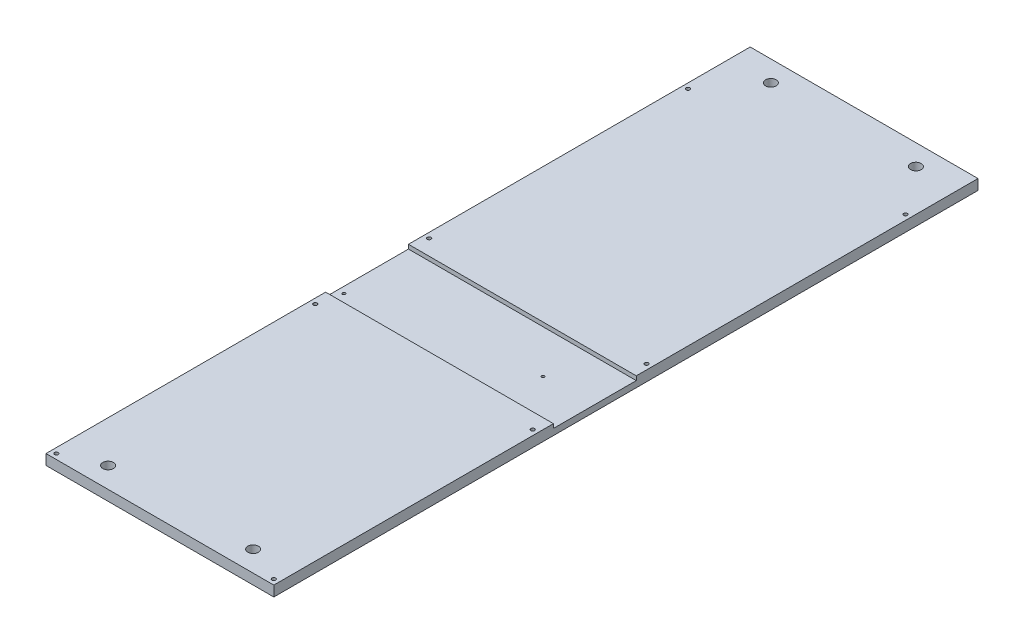
SolidWorks part; units mm, degrees
ref_plane "Front" through (0, 0, 0) normal (0, 0, 1) x (1, 0, 0)
ref_plane "Top" through (0, 0, 0) normal (0, 1, 0) x (1, 0, 0)
ref_plane "Right" through (0, 0, 0) normal (1, 0, 0) x (0, 0, -1)
sketch "Sketch1" plane through (0, 0, 0) normal (0, 1, 0) x (1, 0, 0)
  line L1 (0, 0) -> (139.7, 0)
  line L2 (0, 0) -> (0, 431.8)
  line L3 (0, 431.8) -> (139.7, 431.8)
  line L4 (139.7, 0) -> (139.7, 431.8)
  dimension "D1" = 431.8
  dimension "D2" = 139.7
extrude "Boss-Extrude1" add sketch "Sketch1" along normal blind 6.35
sketch "Sketch3" plane through (0, 6.35, 0) normal (0, 1, 0) x (1, 0, 0)
  line L0 (0, 0) -> (139.7, 0) construction
  line L1 (0, 431.8) -> (0, 0) construction
  line L2 (69.85, 431.8) -> (69.85, 0) construction
  line L3 (139.7, 431.8) -> (0, 431.8) construction
  line L6 (0, 165.1) -> (0, 228.6)
  line L9 (0, 196.85) -> (139.7, 196.85) construction
  circle A0 centre (3.175, 3.175) radius 1.1303
  circle A1 centre (3.175, 161.925) radius 1.1303
  circle A2 centre (3.175, 390.525) radius 1.1303
  circle A3 centre (3.175, 231.775) radius 1.1303
  circle A4 centre (136.525, 3.175) radius 1.1303
  circle A5 centre (136.525, 161.925) radius 1.1303
  circle A6 centre (136.525, 231.775) radius 1.1303
  circle A7 centre (136.525, 390.525) radius 1.1303
  point P24 (0, 0)
  dimension "D1" = 2.2606
  dimension "D2" = 3.175
  dimension "D3" = 3.175
  dimension "D5" = 63.5
  dimension "D4" = 2
extrude "Cut-Extrude6" cut sketch "Sketch3" against normal blind 6.35 contours A0 | A4 | A5 | A6 | A1 | A3 | A2 | A7
sketch "Sketch4" plane through (0, 6.35, 0) normal (0, 1, 0) x (1, 0, 0)
  line L0 (0, 431.8) -> (0, 0) construction
  line L1 (0, 228.6) -> (139.7, 228.6)
  line L2 (0, 228.6) -> (0, 165.1)
  line L3 (0, 165.1) -> (139.7, 165.1)
  line L4 (139.7, 228.6) -> (139.7, 165.1)
  line L5 (139.7, 0) -> (139.7, 431.8) construction
  line L6 (0, 0) -> (139.7, 0) construction
  line L8 (-6.35, 171.45) -> (146.05, 171.45)
  line L9 (-6.35, 171.45) -> (-6.35, 222.25)
  line L10 (-6.35, 222.25) -> (146.05, 222.25)
  line L11 (146.05, 171.45) -> (146.05, 222.25)
  point P14 (-6.35, 196.85)
  point P15 (69.85, 222.25)
  dimension "D1" = 63.5
  dimension "D2" = 165.1
  dimension "D3" = 50.8
  dimension "D4" = 152.4
  dimension "D5" = 31.75
  dimension "D6" = 69.85
extrude "Cut-Extrude7" cut sketch "Sketch4" against normal blind 2.54 contours L10 L2 L8 L4
sketch "Sketch5" plane through (0, 3.81, 0) normal (0, 1, 0) x (1, 0, 0)
  line L0 (0, 171.45) -> (139.7, 171.45) construction
  line L1 (0, 431.8) -> (0, 0) construction
  line L2 (0, 222.25) -> (0, 171.45) construction
  circle A0 centre (3.81, 178.816) radius 0.889
  circle A1 centre (108.966, 195.834) radius 0.889
  dimension "D1" = 1.778
  dimension "D2" = 7.366
  dimension "D3" = 3.81
  dimension "D4" = 1.778
  dimension "D5" = 24.384
  dimension "D6" = 108.966
extrude "Cut-Extrude8" cut sketch "Sketch5" against normal through all
sketch "Sketch6" plane through (0, 6.35, 0) normal (0, 1, 0) x (1, 0, 0)
  line L0 (139.7, 431.8) -> (0, 431.8) construction
  line L1 (0, 431.8) -> (0, 222.25) construction
  line L2 (69.85, 431.8) -> (69.85, 0) construction
  line L3 (0, 0) -> (139.7, 0) construction
  line L4 (69.85, 215.9) -> (94.2364, 215.9) construction
  circle A0 centre (25.4, 419.1) radius 3.2639
  circle A1 centre (114.3, 419.1) radius 3.2639
  circle A2 centre (114.3, 12.7) radius 3.2639
  circle A3 centre (25.4, 12.7) radius 3.2639
  point P13 (69.85, 215.9)
  dimension "D1" = 6.5278
  dimension "D2" = 12.7
  dimension "D3" = 25.4
extrude "Cut-Extrude9" cut sketch "Sketch6" against normal through all
